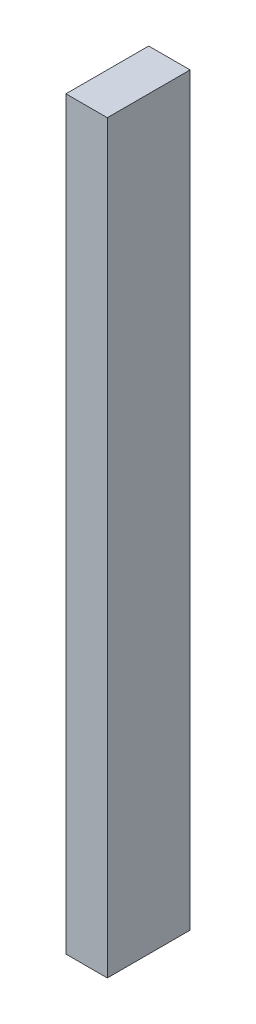
SolidWorks part; units mm, degrees
ref_plane "Front Plane" through (0, 0, 0) normal (0, 0, 1) x (1, 0, 0)
ref_plane "Top Plane" through (0, 0, 0) normal (0, 1, 0) x (1, 0, 0)
ref_plane "Right Plane" through (0, 0, 0) normal (1, 0, 0) x (0, 0, -1)
sketch "Sketch1" plane through (0, 0, 0) normal (1, 0, 0) x (0, 0, -1)
  line L1 (-2, 18) -> (2, 18)
  line L2 (-2, 18) -> (-2, -18)
  line L3 (-2, -18) -> (2, -18)
  line L4 (2, 18) -> (2, -18)
  line L5 (-2, 18) -> (2, -18) construction
  line L6 (-2, -18) -> (2, 18) construction
  point P0 (0, 0)
  dimension "D1" = 4
  dimension "D2" = 36
extrude "Boss-Extrude1" add sketch "Sketch1" along normal blind 2
